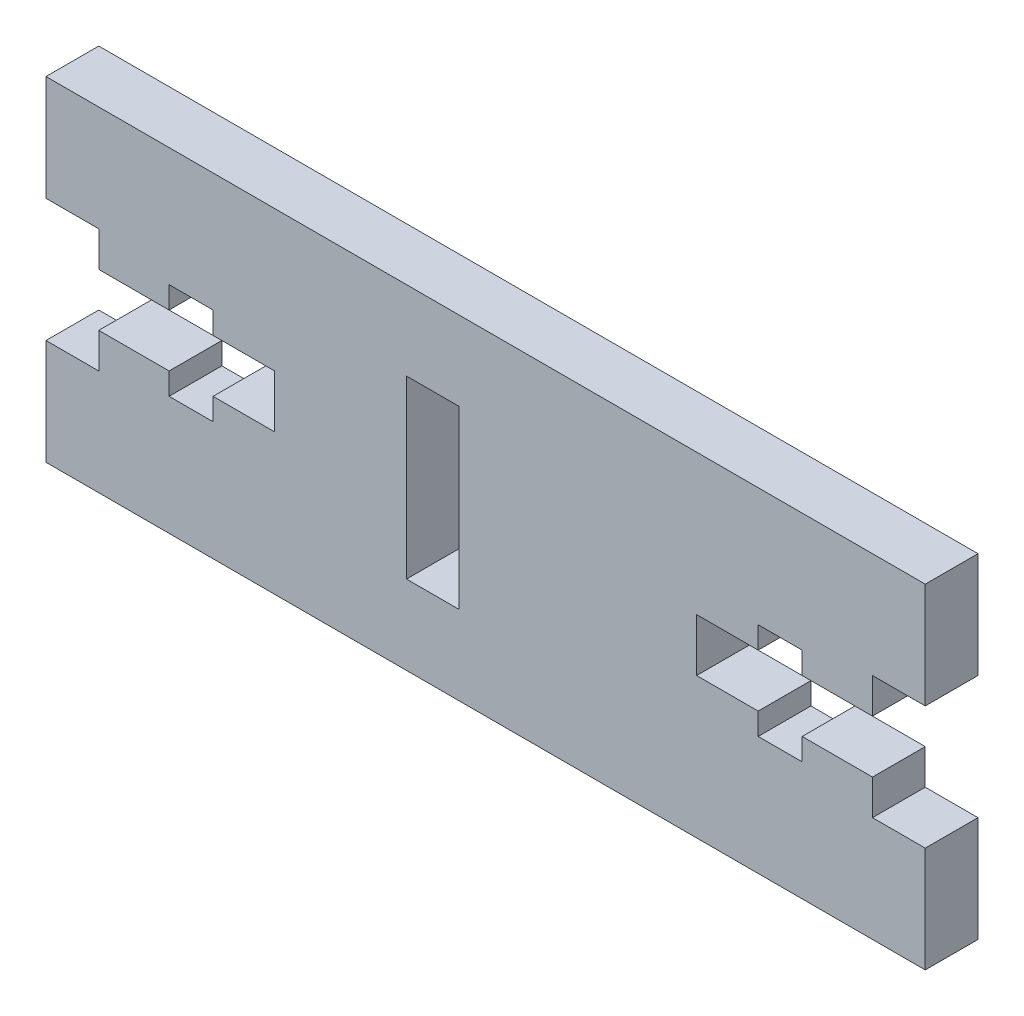
SolidWorks part; units mm, degrees
ref_plane "前视基准面" through (0, 0, 0) normal (0, 0, 1) x (1, 0, 0)
ref_plane "上视基准面" through (0, 0, 0) normal (0, 1, 0) x (1, 0, 0)
ref_plane "右视基准面" through (0, 0, 0) normal (1, 0, 0) x (0, 0, -1)
ref_plane "基准面4" through (0, 0, 3) normal (0, 0, 1) x (1, 0, 0)
sketch "草图1" plane through (0, 0, 3) normal (0, 0, 1) x (1, 0, 0)
  line L0 (45.58, 0) -> (45.58, 6)
  line L1 (45.58, 6) -> (42.58, 6)
  line L2 (42.58, 6) -> (42.58, 7.9995)
  line L3 (42.58, 7.9995) -> (38.581, 7.9995)
  line L4 (38.581, 7.9995) -> (38.581, 6.7496)
  line L5 (38.581, 6.7496) -> (36.0798, 6.7496)
  line L6 (36.0798, 6.7496) -> (36.0798, 7.9995)
  line L7 (36.0798, 7.9995) -> (32.58, 7.9995)
  line L8 (32.58, 7.9995) -> (32.58, 10.9995)
  line L9 (32.58, 10.9995) -> (36.0798, 10.9995)
  line L10 (36.0798, 10.9995) -> (36.0798, 12.2508)
  line L11 (36.0798, 12.2508) -> (38.581, 12.2508)
  line L12 (38.581, 12.2508) -> (38.581, 10.9995)
  line L13 (38.581, 10.9995) -> (42.58, 10.9995)
  line L14 (42.58, 10.9995) -> (42.58, 13.0004)
  line L15 (42.58, 13.0004) -> (45.58, 13.0004)
  line L16 (45.58, 13.0004) -> (45.58, 19.0004)
  line L17 (45.58, 19.0004) -> (-4.4194, 19.0004)
  line L18 (-4.4194, 19.0004) -> (-4.4194, 13.0004)
  line L19 (-4.4194, 13.0004) -> (-1.4194, 13.0004)
  line L20 (-1.4194, 13.0004) -> (-1.4194, 10.9995)
  line L21 (-1.4194, 10.9995) -> (2.5796, 10.9995)
  line L22 (2.5796, 10.9995) -> (2.5796, 12.2508)
  line L23 (2.5796, 12.2508) -> (5.0808, 12.2508)
  line L24 (5.0808, 12.2508) -> (5.0808, 10.9995)
  line L25 (5.0808, 10.9995) -> (8.5806, 10.9995)
  line L26 (8.5806, 10.9995) -> (8.5806, 7.9995)
  line L27 (8.5806, 7.9995) -> (5.0808, 7.9995)
  line L28 (5.0808, 7.9995) -> (5.0808, 6.7496)
  line L29 (5.0808, 6.7496) -> (2.5796, 6.7496)
  line L30 (2.5796, 6.7496) -> (2.5796, 7.9995)
  line L31 (2.5796, 7.9995) -> (-1.4194, 7.9995)
  line L32 (-1.4194, 7.9995) -> (-1.4194, 6)
  line L33 (-1.4194, 6) -> (-4.4194, 6)
  line L34 (-4.4194, 6) -> (-4.4194, 0)
  line L35 (-4.4194, 0) -> (45.58, 0)
  line L36 (16.0803, 14.4997) -> (19.0802, 14.4997)
  line L37 (19.0802, 14.4997) -> (19.0802, 4.5007)
  line L38 (19.0802, 4.5007) -> (16.0803, 4.5007)
  line L39 (16.0803, 4.5007) -> (16.0803, 14.4997)
extrude "凸台-拉伸1" add sketch "草图1" against normal blind 3
